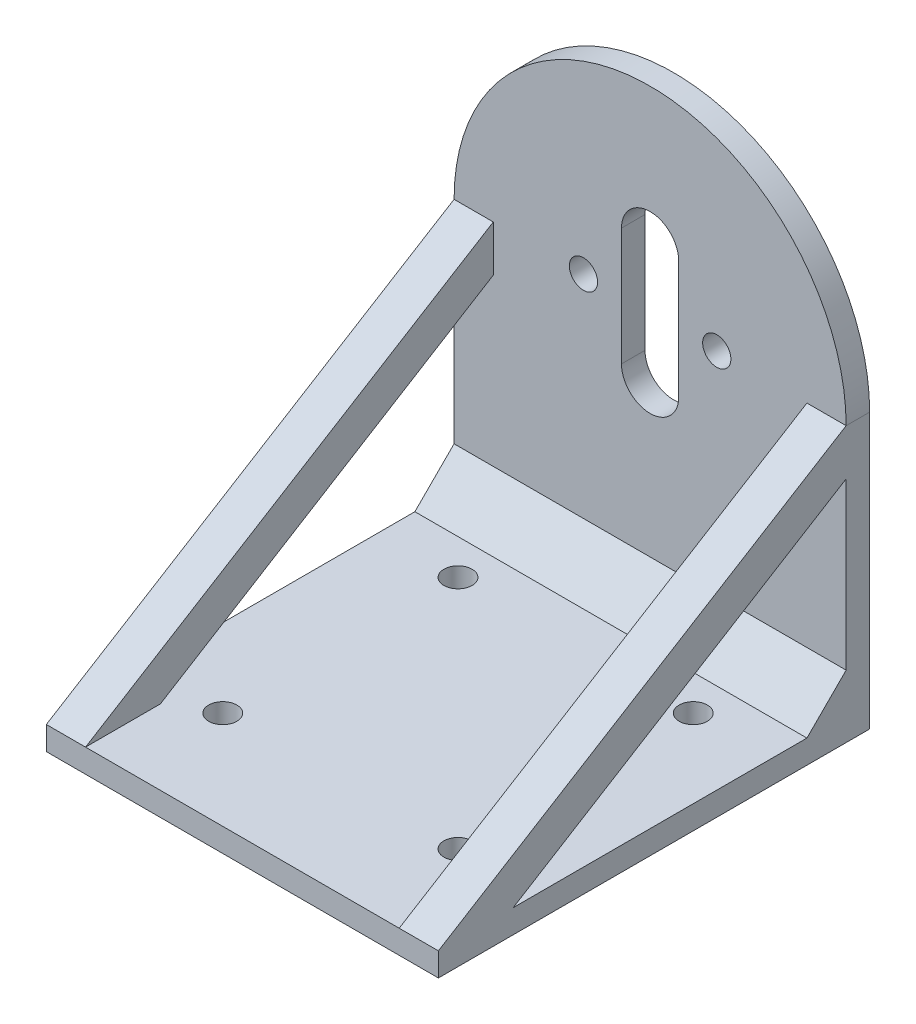
SolidWorks part; units mm, degrees
ref_plane "Front Plane" through (0, 0, 0) normal (0, 0, 1) x (1, 0, 0)
ref_plane "Top Plane" through (0, 0, 0) normal (0, 1, 0) x (1, 0, 0)
ref_plane "Right Plane" through (0, 0, 0) normal (1, 0, 0) x (0, 0, -1)
sketch "Sketch5" plane through (0, 0, 0) normal (0, 0, 1) x (1, 0, 0)
  line L0 (4.1431, 60) -> (47.9796, 60) construction
  line L5 (25, 35) -> (25, 22.5) construction
  line L6 (12.5, 35) -> (37.5, 35) construction
  line L7 (0, 0) -> (0, 35)
  line L8 (0, 0) -> (50, 0)
  line L9 (50, 0) -> (50, 35)
  line L10 (25, 0) -> (25, -19.8941) construction
  line L11 (25, 42.5) -> (25, 27.5) construction
  line L12 (28.65, 42.5) -> (28.65, 27.5)
  line L13 (21.35, 42.5) -> (21.35, 27.5)
  circle A0 centre (25, 35) radius 12.5 construction
  circle A1 centre (25, 35) radius 3.65 construction
  circle A2 centre (16.5, 35) radius 1.8
  circle A3 centre (33.5, 35) radius 1.8
  arc A4 (50, 35) -> (0, 35) centre (25, 35) ccw
  arc A5 (28.65, 42.5) -> (21.35, 42.5) centre (25, 42.5) ccw
  arc A6 (21.35, 27.5) -> (28.65, 27.5) centre (25, 27.5) ccw
  point P18 (25, 0)
  point P23 (25, 35)
  dimension "D1" = 25
  dimension "D2" = 50
  dimension "D3" = 7.3
  dimension "D4" = 17
  dimension "D5" = 3.6
  dimension "D6" = 60
  dimension "D7" = 15
  dimension "D8" = 35
extrude "Boss-Extrude2" add sketch "Sketch5" along normal blind 3 contours A4 L7 L8 L9
sketch "Sketch6" plane through (0, 0, 0) normal (0, -1, 0) x (1, 0, 0)
  line L0 (50, 3) -> (50, 0) construction
  line L1 (0, 0) -> (50, 0)
  line L2 (0, 0) -> (0, 55)
  line L3 (0, 55) -> (50, 55)
  line L4 (50, 0) -> (50, 55)
  dimension "D1" = 55
extrude "Boss-Extrude3" add sketch "Sketch6" against normal blind 3
ref_plane "Plane1" through (25, 0, 0) normal (-1, 0, 0) x (0, 0, 1)
ref_plane "Plane2" through (0, 0, 27.5) normal (0, 0, 1) x (1, 0, 0)
sketch "Sketch7" plane through (0, 0, 0) normal (0, -1, 0) x (1, 0, 0)
  line L0 (0, 27.5) -> (50, 27.5) construction
  line L1 (25, 55) -> (25, 0) construction
  line L4 (0, 0) -> (50, 0)
  line L5 (50, 0) -> (50, 55)
  line L6 (50, 55) -> (0, 55)
  line L7 (0, 55) -> (0, 0)
  line L8 (0, 0) -> (50, 0) construction
  line L9 (50, 0) -> (50, 55) construction
  line L10 (50, 55) -> (0, 55) construction
  line L11 (0, 55) -> (0, 0) construction
  circle A0 centre (10, 42.5) radius 1.5
  point P8 (10, 42.5)
  dimension "D2" = 3
  dimension "D3" = 15
  dimension "D4" = 15
  dimension "D1" = 0
hole_wizard "M3, 3.6mm" positions "Sketch7" profile "Sketch9" hole size "Ø3.0" standard "ANSI Metric" end condition through all
sketch "Sketch9" plane through (10, 0, 42.5) normal (1, 0, 0) x (0, 0, -1)
  line L0 (0, 0) -> (0, 60)
  line L1 (0, 60) -> (1.8, 60)
  line L2 (1.8, 60) -> (1.8, 0)
  line L5 (1.8, 0) -> (0, 0)
  line L11 (0, -6.35) -> (0, 107.95) construction
  dimension "Thru Hole Dia." = 3.6
  dimension "Thru Hole Depth" = 60
mirror "Mirror1" about plane through (25, 0, 0) normal (-1, 0, 0) of "M3, 3.6mm" second plane through (0, 0, 27.5) second plane normal (0, 0, 1)
sketch "Sketch10" plane through (50, 0, 0) normal (1, 0, 0) x (0, 0, -1)
  line L0 (-3, 35) -> (-55, 3)
  line L1 (-55, 3) -> (-45.4598, 3)
  line L2 (-3, 3) -> (-55, 3) construction
  line L3 (-45.4598, 3) -> (-3, 29.1291)
  line L4 (-3, 3) -> (-3, 35) construction
  line L5 (-3, 29.1291) -> (-3, 35)
  dimension "D1" = 5
extrude "Boss-Extrude4" add sketch "Sketch10" against normal blind 5
mirror "Mirror2" about plane through (25, 0, 0) normal (-1, 0, 0) of "Boss-Extrude4"
chamfer "Chamfer1" distance 5 angle 45 1 edges at (25, 3, 3)
equation "\"33。5\"=37.2245"
